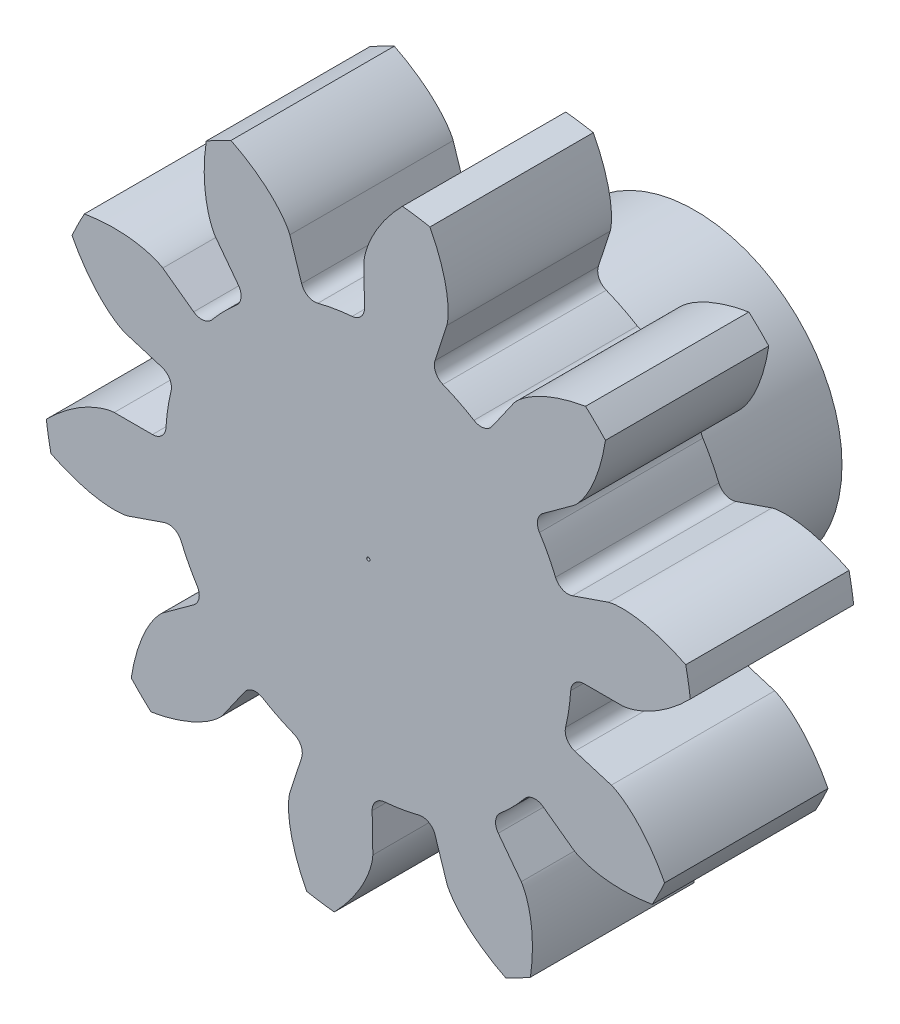
SolidWorks part; units mm, degrees
ref_plane "Front Plane" through (0, 0, 0) normal (0, 0, 1) x (1, 0, 0)
ref_plane "Top Plane" through (0, 0, 0) normal (0, 1, 0) x (1, 0, 0)
ref_plane "Right Plane" through (0, 0, 0) normal (1, 0, 0) x (0, 0, -1)
sketch "Sketch1" plane through (0, 0, 0) normal (0, 0, 1) x (1, 0, 0)
  line L0 (7.7772, 0) -> (6.2072, 0)
  line L1 (9.7951, 1.6405) -> (-9.7951, -1.6405)
  line L2 (0, 0) -> (8.2754, 0.1233) construction
  circle A0 centre (0, 0) radius 7.7772 construction
  circle A1 centre (0, 0) radius 9.9316
  circle A2 centre (0, 0) radius 6.2072
  circle A3 centre (0, 0) radius 8.2763 construction
  spline S0 degree 4 poles (7.7772, 0) (7.7829, 0.0001) (7.799, 0.0008) (7.8294, 0.0037) (7.8788, 0.0104) (7.9414, 0.0221) (8.0217, 0.0407) (8.1153, 0.0671) (8.2171, 0.1007) (8.3264, 0.1423) (8.4342, 0.1882) (8.5402, 0.2379) (8.6445, 0.291) (8.7691, 0.3595) (8.916, 0.4473) (9.0837, 0.5581) (9.2689, 0.6933) (9.4519, 0.8409) (9.6271, 0.9941) (9.798, 1.1577) (9.9591, 1.3222) (10.1196, 1.5016) (10.2644, 1.6715) (10.4187, 1.871) (10.541, 2.0346) (10.6935, 2.2595) (10.7809, 2.395) (10.8801, 2.5566) (10.9225, 2.6299) (10.9486, 2.675) knots 0 0 0 0 0 0.005377 0.015084 0.028532 0.04661 0.064855 0.092111 0.119476 0.146842 0.174209 0.201575 0.228941 0.256307 0.307035 0.361767 0.4165 0.471232 0.525964 0.580697 0.635429 0.690161 0.744894 0.799626 0.854358 0.909091 0.954545 1 1 1 1 1 construction
  spline S1 degree 4 poles (7.7772, 0) (7.7829, 0.0001) (7.799, 0.0008) (7.8294, 0.0037) (7.8788, 0.0104) (7.9414, 0.0221) (8.0217, 0.0407) (8.1153, 0.0671) (8.2171, 0.1007) (8.3264, 0.1423) (8.4342, 0.1882) (8.5402, 0.2379) (8.6445, 0.291) (8.7691, 0.3595) (8.916, 0.4473) (9.0837, 0.5581) (9.2689, 0.6933) (9.4519, 0.8409) (9.6271, 0.9941) (9.798, 1.1577) (9.9591, 1.3222) (10.1196, 1.5016) (10.2644, 1.6715) (10.4187, 1.871) (10.541, 2.0346) (10.6604, 2.2107) (10.7175, 2.2975) (10.7463, 2.3422) knots 0 0 0 0 0 0.005377 0.015084 0.028532 0.04661 0.064855 0.092111 0.119476 0.146842 0.174209 0.201575 0.228941 0.256307 0.307035 0.361767 0.4165 0.471232 0.525964 0.580697 0.635429 0.690161 0.744894 0.799626 0.854358 0.909091 0.909091 0.909091 0.909091 0.909091
  dimension "D1" = 15.5544
  dimension "D2" = 19.8631
  dimension "D3" = 12.4145
  dimension "D5" = 16.5526
  dimension "D4" = 8.654
extrude "Boss-Extrude3" add sketch "Sketch1" along normal blind 5 contours L1 A2 | A2 L1 | L0 S1 A1 L1 A2
mirror "Mirror2" about plane through (0, 0, 5) normal (0.1652, -0.9863, 0) of "Boss-Extrude3"
fillet "Fillet1" radius 0.4138 2 edges at (5.8685, 2.0225, 2.5) (6.2072, 0, 2.5)
pattern_circular "CirPattern8" count 10 over 360 about axis through (0, 0, 5) along (0, 0, -1) of "Boss-Extrude3", "Mirror2", "Fillet1"
sketch "Sketch3" plane through (0, 0, 5) normal (0, 0, 1) x (1, 0, 0)
  circle A0 centre (0, 0) radius 0.05
  dimension "D1" = 0.1
extrude "Cut-Extrude2" cut sketch "Sketch3" against normal through all
sketch "Esquisse1" plane through (0, 0, 0) normal (0, 0, -1) x (-1, 0, 0)
  circle A0 centre (0, -0.2523) radius 4.5
  dimension "D1" = 9
extrude "Boss.-Extru.1" add sketch "Esquisse1" along normal blind 5
sketch "Esquisse2" plane through (0, 0, -5) normal (0, 0, -1) x (-1, 0, 0)
  circle A0 centre (0, 0) radius 3
  dimension "D1" = 6
extrude "Enlèv. mat.-Extru.1" cut sketch "Esquisse2" against normal blind 5
equation "\"d\"= ( \"N\" * 2.6 * 4 ) / ( 2 * 3.1415 )'Pitch diameter"
equation "\"N\"= 10'Number of teeth"
equation "\"bl\"= 0.1mm'Backlash"
equation "\"pa\"= 20deg'Pressure angle (deg)"
equation "\"pc\"= ( 3.1415 * \"d\" ) / \"N\"'Circular pitch"
equation "\"m\"= \"d\" / \"N\"\t\t\t'module"
equation "\"P\"= \"N\" / \"d\"'Diametral pitch"
equation "\"a\"= 1/\"P\"\t\t\t'Addendum distance"
equation "\"b\"= 1.25 / \"P\"'Dedendum distance"
equation "\"rb\"= (\"d\"/2)*cos(\"pa\")\t\t'base circle radius"
equation "\"cp\"= 3.1415/\"P\"\t\t'Circular pitch"
equation "\"t\"= ( \"cp\" / 2 ) - \"bl\"'tooth tickness"
equation "\"c\"=\"b\"-\"a\"\t\t\t'Clearance"
equation "\"facewidth\"= 5mm'face width"
equation "\"rbd\"= \"rb\" * 2'base circle diameter"
equation "\"D1@Sketch1\"=\"rbd\""
equation "\"D2@Sketch1\"= \"d\" + (\"a\" * 2)"
equation "\"D3@Sketch1\" = \"ded\""
equation "\"D4@Sketch1\"= ((\"t\" /2) / (\"d\"/2)) * (180/3.1415)"
equation "\"D1@Boss-Extrude3\"=\"facewidth\""
equation "\"D1@Fillet1\"=\"c\""
equation "\"D1@CirPattern8\"=\"N\""
equation "\"D5@Sketch1\"=\"d\""
equation "\"ded1\"= \"d\" - 2 * ( ( ( \"d\" / 2 ) - \"rb\" ) + ( 0.5 * ( 1.25 / \"P\" ) ) )"
equation "\"ded2\"= \"d\" - ( \"b\" * 2 )"
equation "\"ded\"= IIF ( \"rb\" < ( \"ded2\" / 2 ) , \"ded1\" , \"ded2\" )"
equation "\"shaftdia\"= 0.1mm"
equation "\"D1@Sketch3\"=\"shaftdia\""
